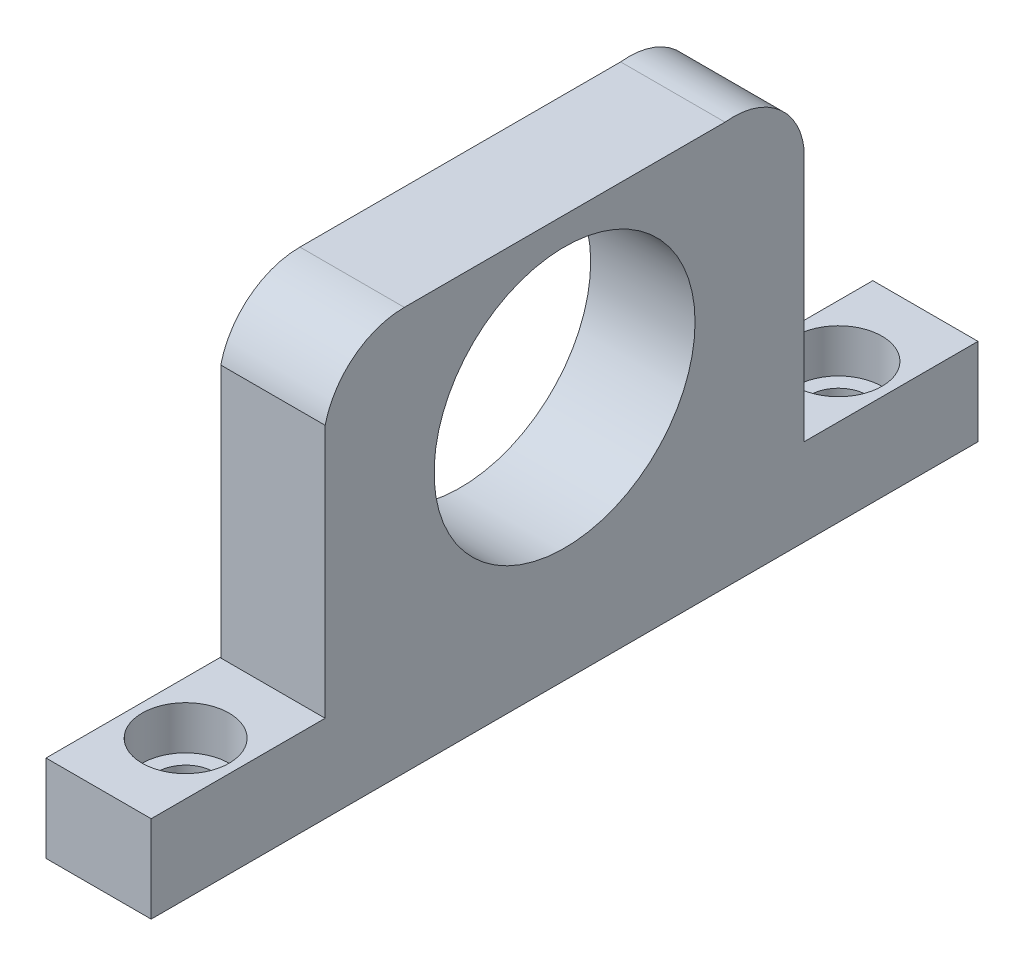
SolidWorks part; units mm, degrees
ref_plane "Front Plane" through (0, 0, 0) normal (0, 0, 1) x (1, 0, 0)
ref_plane "Top Plane" through (0, 0, 0) normal (0, 1, 0) x (1, 0, 0)
ref_plane "Right Plane" through (0, 0, 0) normal (1, 0, 0) x (0, 0, -1)
sketch "Sketch1" plane through (0, 0, 0) normal (0, 1, 0) x (1, 0, 0)
  line L13 (0, 23.8353) -> (0, 4.8253)
  line L15 (-2.418, 4.8253) -> (-2.418, 23.8353)
  line L16 (-2.418, 4.8253) -> (0, 4.8253)
  line L17 (-2.418, 23.8353) -> (0, 23.8353)
  circle A0 centre (-1.208, 6.8253) radius 0.655
  circle A1 centre (-1.208, 21.8353) radius 0.655
  dimension "D1" = 1.31
  dimension "D3" = 1.31
  dimension "D2" = 15.01
extrude "Boss-Extrude1" add sketch "Sketch1" along normal blind 2
sketch "Sketch2" plane through (0, 2, 0) normal (0, 1, 0) x (1, 0, 0)
  circle A0 centre (-1.208, 21.8353) radius 1
  circle A1 centre (-1.208, 6.8253) radius 1
  dimension "D1" = 2
  dimension "D2" = 2
extrude "Cut-Extrude1" cut sketch "Sketch2" against normal blind 1
sketch "Sketch4" plane through (0, 0, 0) normal (1, 0, 0) x (0, 0, -1)
  line L1 (4.8253, 2) -> (23.8353, 2) construction
  line L4 (19.8353, 2) -> (8.8253, 2)
  line L5 (19.8353, 2) -> (19.8353, 7.8335)
  line L6 (18.0195, 9.2721) -> (10.6453, 9.2721)
  line L7 (8.8253, 2) -> (8.8253, 7.8335)
  circle A0 centre (14.3303, 5.636) radius 3
  arc A1 (18.0195, 9.2721) -> (19.8353, 7.8335) centre (18.2115, 7.6492) cw
  arc A2 (8.8253, 7.8335) -> (10.6453, 9.2721) centre (10.6453, 7.4015) cw
  dimension "D1" = 6
extrude "Boss-Extrude3" add sketch "Sketch4" against normal blind 2.4
